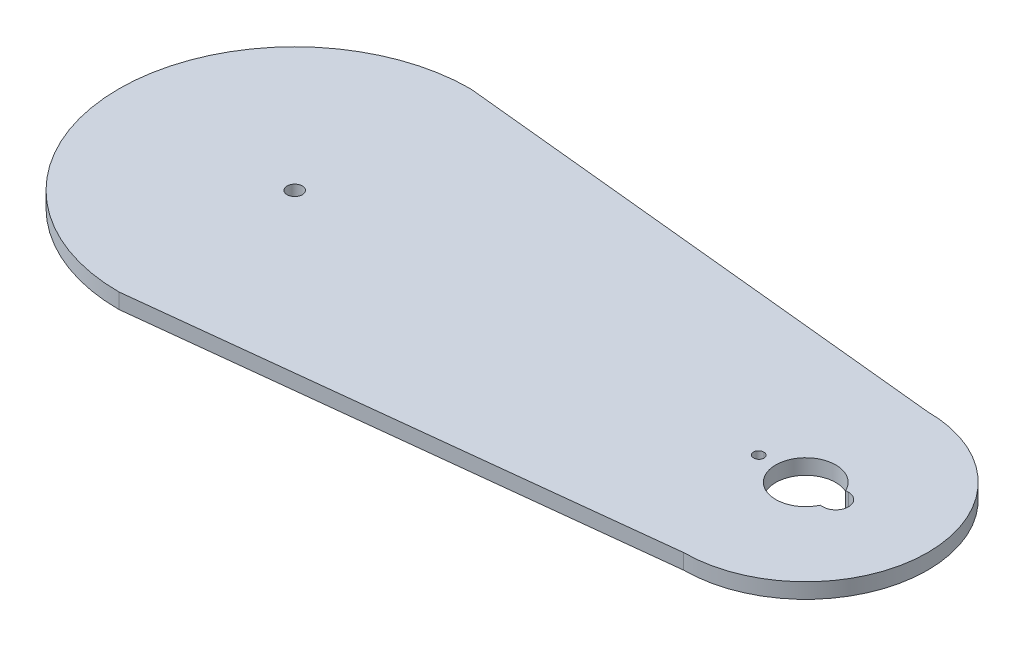
SolidWorks part; units mm, degrees
ref_plane "Front Plane" through (0, 0, 0) normal (0, 0, 1) x (1, 0, 0)
ref_plane "Top Plane" through (0, 0, 0) normal (0, 1, 0) x (1, 0, 0)
ref_plane "Right Plane" through (0, 0, 0) normal (1, 0, 0) x (0, 0, -1)
sketch "Sketch2" plane through (0, 0, 0) normal (0, 1, 0) x (1, 0, 0)
  line L5 (-100, 58.0616) -> (0, 48)
  line L6 (0, 0) -> (-100, -11.1458)
  arc A0 (0, 48) -> (0, 0) centre (0, 24) cw
  arc A1 (-100, 58.0616) -> (-100, -11.1458) centre (-100, 23.4579) ccw
  dimension "D2" = 24
  dimension "D3" = 34.6037
extrude "Boss-Extrude2" add sketch "Sketch2" along normal blind 3
sketch "Sketch3" plane through (0, 3, 0) normal (0, 1, 0) x (1, 0, 0)
  line L1 (5.3442, 26.5) -> (5.9, 26.5)
  line L3 (5.9, 21.5) -> (5.3442, 21.5)
  arc A0 (5.3442, 26.5) -> (5.3442, 21.5) centre (0, 24) ccw
  arc A1 (0, 0) -> (0, 48) centre (0, 24) ccw construction
  arc A2 (5.9, 26.5) -> (5.9, 21.5) centre (5.9, 24) cw
  dimension "D1" = 11.8
  dimension "D2" = 5
  dimension "D4" = 2.5
  dimension "D3" = 0.5558
sketch "Sketch6" plane through (0, 3, 0) normal (0, 1, 0) x (1, 0, 0)
  circle A0 centre (-100, 23.4579) radius 1.5
  circle A1 centre (0, 24) radius 1.5
  arc A2 (-100, 58.0616) -> (-100, -11.1458) centre (-100, 23.4579) ccw construction
  arc A3 (0, 0) -> (0, 48) centre (0, 24) ccw construction
  dimension "D1" = 3
sketch "Sketch7" plane through (0, 3, 0) normal (0, 1, 0) x (1, 0, 0)
  line L0 (5.3442, 26.5) -> (5.9042, 26.5)
  line L2 (5.9042, 21.5) -> (5.3442, 21.5)
  arc A0 (5.3442, 26.5) -> (5.3442, 21.5) centre (0, 24) ccw
  arc A1 (5.9042, 26.5) -> (5.9042, 21.5) centre (5.9042, 24) cw
  dimension "D1" = 11.8
  dimension "D2" = 5
  dimension "D3" = 0.56
extrude "Cut-Extrude4" cut sketch "Sketch7" against normal blind 10
sketch "Sketch8" plane through (0, 3, 0) normal (0, 1, 0) x (1, 0, 0)
  circle A0 centre (-9.2, 24) radius 1
  dimension "D1" = 2
  dimension "D2" = 9.2
extrude "Cut-Extrude5" cut sketch "Sketch8" against normal blind 10
extrude "Cut-Extrude6" cut sketch "Sketch6" against normal blind 10 contours A0
extrude "Cut-Extrude2" cut sketch "Sketch3" against normal blind 3
sketch "Sketch5" plane through (0, 3, 0) normal (0, 1, 0) x (1, 0, 0)
  circle A0 centre (-9.3, 24) radius 1
  circle A1 centre (0, 24) radius 5.9 construction
  arc A2 (0, 0) -> (0, 48) centre (0, 24) ccw construction
  point P10 (24, 24)
  dimension "D1" = 2
  dimension "D2" = 9.3
extrude "Cut-Extrude3" cut sketch "Sketch5" against normal blind 3
